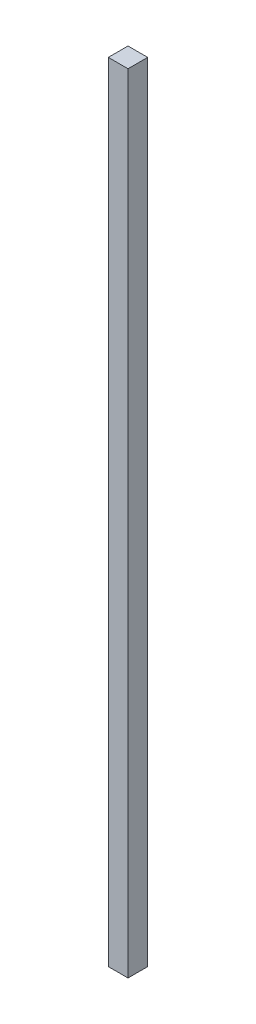
SolidWorks part; units mm, degrees
material "Alloy Steel"
ref_plane "Front Plane" through (0, 0, 0) normal (0, 0, 1) x (1, 0, 0)
ref_plane "Top Plane" through (0, 0, 0) normal (0, 1, 0) x (1, 0, 0)
ref_plane "Right Plane" through (0, 0, 0) normal (1, 0, 0) x (0, 0, -1)
sketch "Sketch1" plane through (0, 0, 0) normal (0, 1, 0) x (1, 0, 0)
  line L1 (-1.5875, 1.5875) -> (1.5875, 1.5875)
  line L2 (-1.5875, 1.5875) -> (-1.5875, -1.5875)
  line L3 (-1.5875, -1.5875) -> (1.5875, -1.5875)
  line L4 (1.5875, 1.5875) -> (1.5875, -1.5875)
  line L5 (-1.5875, 1.5875) -> (1.5875, -1.5875) construction
  line L6 (-1.5875, -1.5875) -> (1.5875, 1.5875) construction
  point P0 (0, 0)
  dimension "D1" = 3.175
extrude "Boss-Extrude1" add sketch "Sketch1" along normal blind 127
